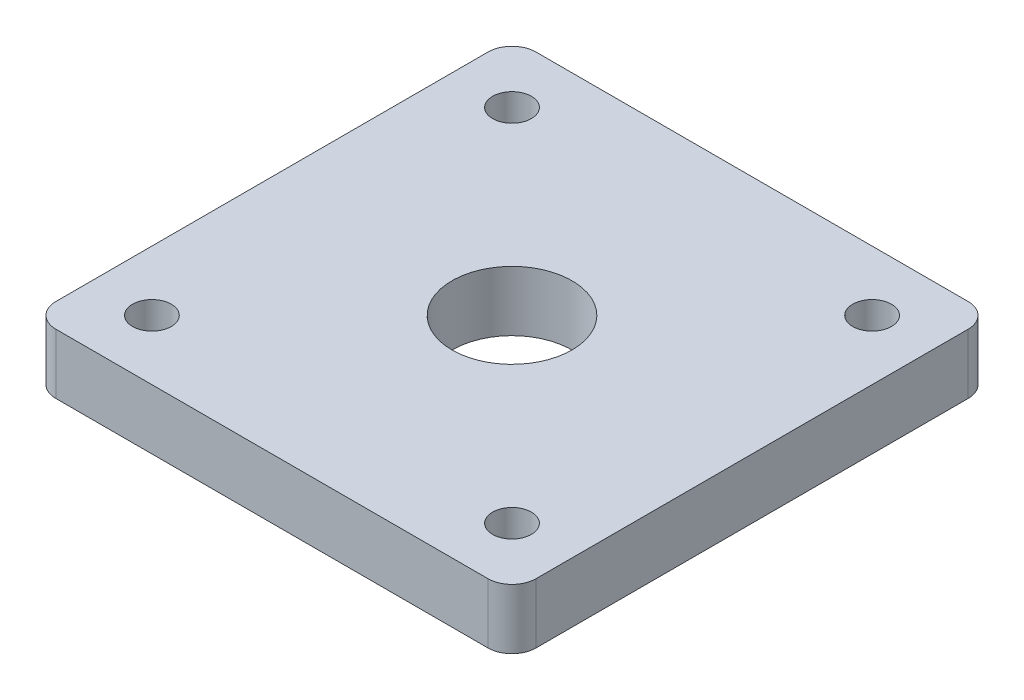
SolidWorks part; units mm, degrees
ref_plane "Front Plane" through (0, 0, 0) normal (0, 0, 1) x (1, 0, 0)
ref_plane "Top Plane" through (0, 0, 0) normal (0, 1, 0) x (1, 0, 0)
ref_plane "Right Plane" through (0, 0, 0) normal (1, 0, 0) x (0, 0, -1)
sketch "Sketch2" plane through (0, 0, 0) normal (0, 1, 0) x (1, 0, 0)
  line L1 (-22.86, -25.4) -> (22.86, -25.4)
  line L2 (-25.4, -22.86) -> (-25.4, 22.86)
  line L3 (-22.86, 25.4) -> (22.86, 25.4)
  line L4 (25.4, -22.86) -> (25.4, 22.86)
  line L5 (-25.4, -25.4) -> (25.4, 25.4) construction
  line L6 (-25.4, 25.4) -> (25.4, -25.4) construction
  line L7 (-25.4, 25.4) -> (-19.05, 25.4)
  line L8 (-25.4, 25.4) -> (-25.4, 19.05)
  line L9 (-25.4, 19.05) -> (-19.05, 19.05) construction
  line L10 (-19.05, 25.4) -> (-19.05, 19.05) construction
  circle A0 centre (-19.05, 19.05) radius 2.05
  circle A1 centre (0, 0) radius 6.35
  circle A2 centre (19.05, 19.05) radius 2.05
  circle A3 centre (19.05, -19.05) radius 2.05
  circle A4 centre (-19.05, -19.05) radius 2.05
  arc A5 (-22.86, -25.4) -> (-25.4, -22.86) centre (-22.86, -22.86) cw
  arc A6 (22.86, -25.4) -> (25.4, -22.86) centre (22.86, -22.86) ccw
  arc A7 (22.86, 25.4) -> (25.4, 22.86) centre (22.86, 22.86) cw
  arc A8 (-25.4, 22.86) -> (-22.86, 25.4) centre (-22.86, 22.86) cw
  point P0 (0, 0)
  dimension "D5" = 4.1
  dimension "D6" = 12.7
  dimension "D9" = 2.54
  dimension "D1" = 50.8
  dimension "D2" = 50.8
  dimension "D3" = 6.35
  dimension "D4" = 6.35
  dimension "D7" = 2
  dimension "D8" = 2
extrude "Boss-Extrude1" add sketch "Sketch2" along normal blind 6.35 contours A8 L2 A5 L1 A6 L4 A7 L3 A4 A3 A2 A1 A0
